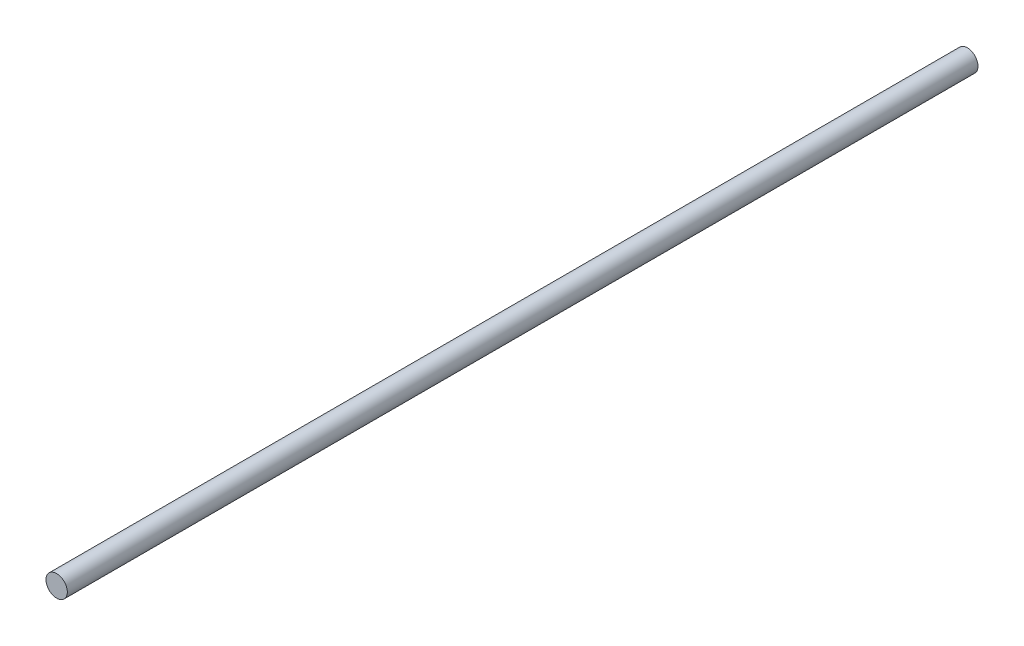
SolidWorks part; units mm, degrees
ref_plane "정면" through (0, 0, 0) normal (0, 0, 1) x (1, 0, 0)
ref_plane "윗면" through (0, 0, 0) normal (0, 1, 0) x (1, 0, 0)
ref_plane "우측면" through (0, 0, 0) normal (1, 0, 0) x (0, 0, -1)
sketch "스케치1" plane through (0, 0, 0) normal (0, 0, 1) x (1, 0, 0)
  circle A0 centre (0, 0) radius 3
  dimension "D1" = 6
extrude "보스-돌출1" add sketch "스케치1" along normal blind 256
